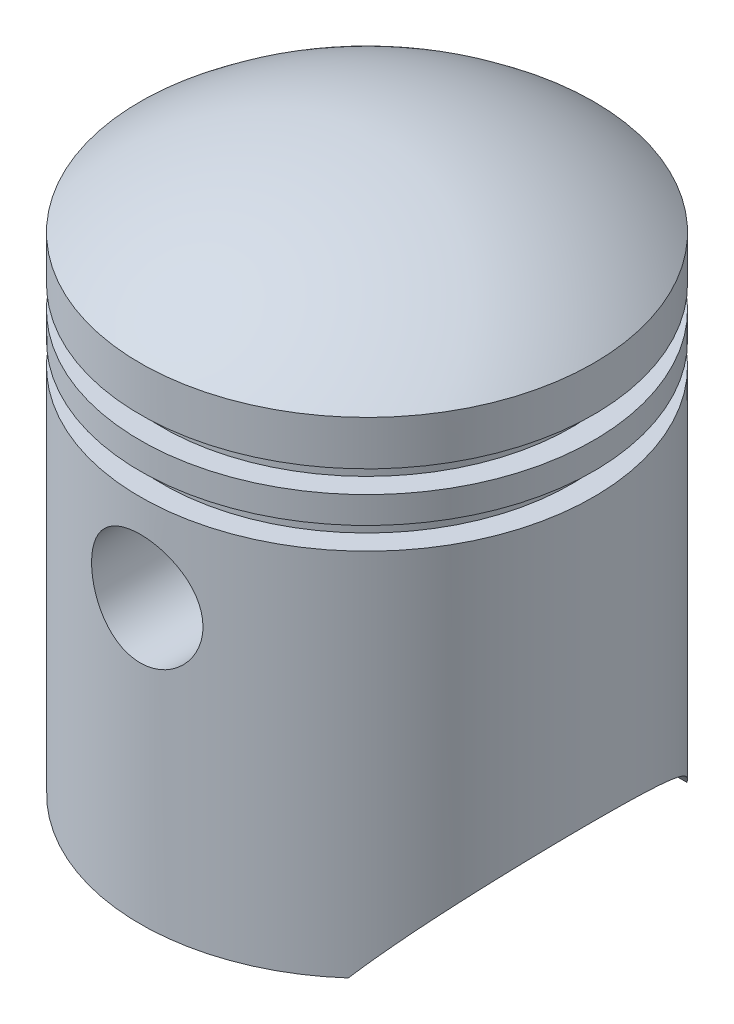
SolidWorks part; units mm, degrees
material "Zinc AC43A (Zn-4Al-2.5Cu-0.04Mg; Number 2 Die Casting Alloy; Zamak 2), Die Cast"
ref_plane "Front Plane" through (0, 0, 0) normal (0, 0, 1) x (1, 0, 0)
ref_plane "Top Plane" through (0, 0, 0) normal (0, 1, 0) x (1, 0, 0)
ref_plane "Right Plane" through (0, 0, 0) normal (1, 0, 0) x (0, 0, -1)
sketch "Sketch1" plane through (0, 0, 0) normal (0, 0, 1) x (1, 0, 0)
  line L0 (25.4326, 0) -> (25.4326, 41.5)
  line L1 (25.4326, 41.5) -> (22.9326, 41.5)
  line L2 (22.9326, 41.5) -> (22.9326, 44)
  line L3 (22.9326, 44) -> (25.4326, 44)
  line L4 (25.4326, 44) -> (25.4326, 47)
  line L5 (25.4326, 47) -> (22.9326, 47)
  line L6 (22.9326, 47) -> (22.9326, 49.5)
  line L7 (22.9326, 49.5) -> (25.4326, 49.5)
  line L8 (25.4326, 49.5) -> (25.4326, 54.5)
  line L9 (23.4326, 0) -> (23.4326, 39.5)
  line L10 (23.4326, 39.5) -> (20.9326, 39.5)
  line L11 (20.9326, 39.5) -> (20.9326, 45.5)
  line L12 (20.9326, 45.5) -> (20.9326, 45.5)
  line L13 (20.9326, 45.5) -> (20.9326, 45.5)
  line L14 (20.9326, 45.5) -> (20.9326, 45.5)
  line L15 (20.9326, 45.5) -> (20.9326, 51.5)
  line L16 (20.9326, 51.5) -> (23.4326, 51.5)
  line L17 (23.4326, 51.5) -> (23.4326, 53.5414)
  line L18 (0, 63.6263) -> (0, 61.6263)
  line L19 (0, 0) -> (0, 61.6263) construction
  line L20 (23.4326, 0) -> (25.4326, 0)
  arc A0 (25.4326, 54.5) -> (0, 63.6263) centre (0, 23.6263) ccw
  arc A1 (23.4326, 53.5414) -> (0, 61.6263) centre (0, 23.6263) ccw
  point P20 (0, 0)
  point P23 (28.9108, 53.7736)
  point P24 (25.4326, 54.5)
  dimension "D6" = 40
  dimension "D1" = 41.5
  dimension "D2" = 2.5
  dimension "D3" = 3
  dimension "D4" = 5
  dimension "D5" = 2
  dimension "D7" = 2.5
revolve "Revolve1" add sketch "Sketch1" angle 360 about L19
sketch "Sketch2" plane through (0, 0, 0) normal (1, 0, 0) x (0, 0, -1)
  line L1 (-25.4326, 0) -> (25.4326, 0) construction
  line L2 (-19, 0) -> (19, 0)
  arc A0 (-19, 0) -> (19, 0) centre (0, -13.05) cw
  point P3 (0, 10)
  dimension "D2" = 10
  dimension "D1" = 38
extrude "Cut-Extrude1" cut sketch "Sketch2" against normal mid plane 70
sketch "Sketch3" plane through (0, 0, 0) normal (0, 0, 1) x (1, 0, 0)
  line L0 (0, 63.6263) -> (0, 31.6263) construction
  circle A0 centre (0, 31.6263) radius 6.25
  arc A1 (25.4326, 54.5) -> (-25.4326, 54.5) centre (0, 23.6263) ccw construction
  dimension "D2" = 12.5
  dimension "D1" = 32
extrude "Cut-Extrude2" cut sketch "Sketch3" against normal mid plane 70
ref_plane "Plane1" through (0, 0, 11) normal (0, 0, 1) x (1, 0, 0)
sketch "Sketch4" plane through (0, 0, 11) normal (0, 0, 1) x (1, 0, 0)
  circle A0 centre (0, 31.6263) radius 7.25
  circle A1 centre (0, 31.6263) radius 6.25 construction
  circle A2 centre (0, 31.6263) radius 6.25
  dimension "D1" = 14.5
extrude "Boss-Extrude1" add sketch "Sketch4" along normal up to surface (11.2828 mm away)
mirror "Mirror1" about plane through (0, 0, 0) normal (0, 0, 1) of "Boss-Extrude1"
